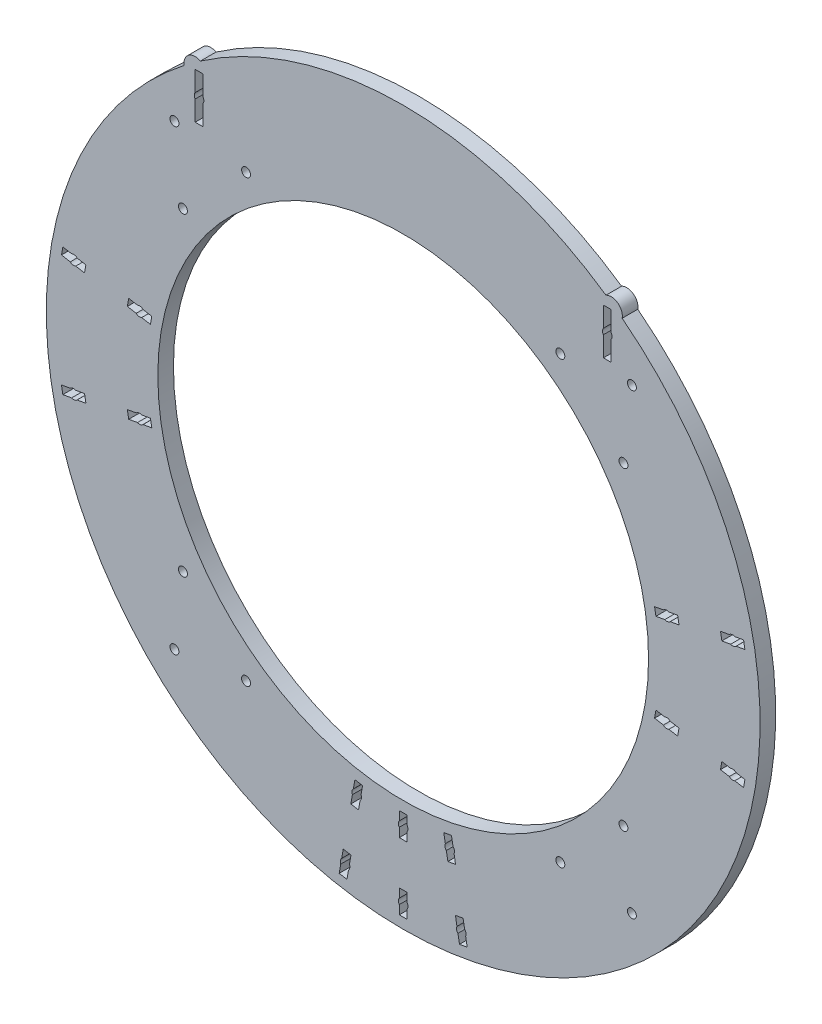
SolidWorks part; units mm, degrees
ref_plane "前视基准面" through (0, 0, 0) normal (0, 0, 1) x (1, 0, 0)
ref_plane "上视基准面" through (0, 0, 0) normal (0, 1, 0) x (1, 0, 0)
ref_plane "右视基准面" through (0, 0, 0) normal (1, 0, 0) x (0, 0, -1)
other "Configuration Table"
sketch "草图1" plane through (0, 0, 0) normal (0, 0, 1) x (1, 0, 0)
  circle A0 centre (0, 0) radius 160
  circle A1 centre (0, 0) radius 110
  dimension "D1" = 320
  dimension "D2" = 220
extrude "凸台-拉伸1" add sketch "草图1" along normal mid plane 7
sketch "草图2" plane through (0, 0, 0) normal (0, 0, 1) x (1, 0, 0)
  line L0 (-1000, 0) -> (49000, 0) construction
  line L1 (0, -1000) -> (0, 49000) construction
  line L2 (-1.75, 148.751) -> (-1.75, 144.75)
  line L3 (-1.75, 155.25) -> (1.75, 155.25)
  line L4 (-1.75, 155.25) -> (-1.75, 151.249)
  line L5 (-1.75, 144.75) -> (1.75, 144.75)
  line L6 (1.75, 155.25) -> (1.75, 151.249)
  line L7 (-1.75, 155.25) -> (1.75, 144.75) construction
  line L8 (-1.75, 144.75) -> (1.75, 155.25) construction
  line L9 (-1.75, 125.25) -> (1.75, 125.25)
  line L10 (-1.75, 125.25) -> (-1.75, 121.249)
  line L11 (-1.75, 114.75) -> (1.75, 114.75)
  line L12 (1.75, 125.25) -> (1.75, 121.249)
  line L13 (-1.75, 125.25) -> (1.75, 114.75) construction
  line L14 (-1.75, 114.75) -> (1.75, 125.25) construction
  line L15 (1.75, 148.751) -> (1.75, 144.75)
  line L16 (-1.75, 118.751) -> (-1.75, 114.75)
  line L17 (1.75, 118.751) -> (1.75, 114.75)
  line L18 (125.25, 1.75) -> (125.25, -1.75)
  line L19 (125.25, -1.75) -> (121.249, -1.75)
  line L20 (118.751, -1.75) -> (114.75, -1.75)
  line L21 (114.75, 1.75) -> (114.75, -1.75)
  line L22 (118.751, 1.75) -> (114.75, 1.75)
  line L23 (125.25, 1.75) -> (121.249, 1.75)
  line L24 (155.25, 1.75) -> (151.249, 1.75)
  line L25 (148.751, 1.75) -> (144.75, 1.75)
  line L26 (144.75, 1.75) -> (144.75, -1.75)
  line L27 (148.751, -1.75) -> (144.75, -1.75)
  line L28 (155.25, -1.75) -> (151.249, -1.75)
  line L29 (155.25, 1.75) -> (155.25, -1.75)
  line L30 (1.75, -125.25) -> (-1.75, -125.25)
  line L31 (-1.75, -125.25) -> (-1.75, -121.249)
  line L32 (-1.75, -118.751) -> (-1.75, -114.75)
  line L33 (1.75, -114.75) -> (-1.75, -114.75)
  line L34 (1.75, -118.751) -> (1.75, -114.75)
  line L35 (1.75, -125.25) -> (1.75, -121.249)
  line L36 (1.75, -155.25) -> (1.75, -151.249)
  line L37 (1.75, -148.751) -> (1.75, -144.75)
  line L38 (1.75, -144.75) -> (-1.75, -144.75)
  line L39 (-1.75, -148.751) -> (-1.75, -144.75)
  line L40 (-1.75, -155.25) -> (-1.75, -151.249)
  line L41 (1.75, -155.25) -> (-1.75, -155.25)
  line L42 (-125.25, -1.75) -> (-125.25, 1.75)
  line L43 (-125.25, 1.75) -> (-121.249, 1.75)
  line L44 (-118.751, 1.75) -> (-114.75, 1.75)
  line L45 (-114.75, -1.75) -> (-114.75, 1.75)
  line L46 (-118.751, -1.75) -> (-114.75, -1.75)
  line L47 (-125.25, -1.75) -> (-121.249, -1.75)
  line L48 (-155.25, -1.75) -> (-151.249, -1.75)
  line L49 (-148.751, -1.75) -> (-144.75, -1.75)
  line L50 (-144.75, -1.75) -> (-144.75, 1.75)
  line L51 (-148.751, 1.75) -> (-144.75, 1.75)
  line L52 (-155.25, 1.75) -> (-151.249, 1.75)
  line L53 (-155.25, -1.75) -> (-155.25, 1.75)
  line L54 (0, 0) -> (1.75, 114.75) construction
  line L55 (25.2355, 153.1953) -> (24.5407, 149.2551)
  line L56 (24.1069, 146.795) -> (23.4122, 142.8548)
  line L57 (23.4122, 142.8548) -> (26.859, 142.247)
  line L58 (27.5538, 146.1873) -> (26.859, 142.247)
  line L59 (28.6823, 152.5875) -> (27.9875, 148.6473)
  line L60 (25.2355, 153.1953) -> (28.6823, 152.5875)
  line L61 (20.026, 123.6511) -> (23.4728, 123.0433)
  line L62 (23.4728, 123.0433) -> (22.7781, 119.1031)
  line L63 (22.3443, 116.643) -> (21.6495, 112.7028)
  line L64 (18.2027, 113.3106) -> (21.6495, 112.7028)
  line L65 (18.8975, 117.2508) -> (18.2027, 113.3106)
  line L66 (20.026, 123.6511) -> (19.3313, 119.7108)
  line L67 (123.6511, -20.026) -> (123.0433, -23.4728)
  line L68 (123.0433, -23.4728) -> (119.1031, -22.7781)
  line L69 (116.643, -22.3443) -> (112.7028, -21.6495)
  line L70 (113.3106, -18.2027) -> (112.7028, -21.6495)
  line L71 (117.2508, -18.8975) -> (113.3106, -18.2027)
  line L72 (123.6511, -20.026) -> (119.7108, -19.3313)
  line L73 (153.1953, -25.2355) -> (149.2551, -24.5407)
  line L74 (146.795, -24.1069) -> (142.8548, -23.4122)
  line L75 (142.8548, -23.4122) -> (142.247, -26.859)
  line L76 (146.1873, -27.5538) -> (142.247, -26.859)
  line L77 (152.5875, -28.6823) -> (148.6473, -27.9875)
  line L78 (153.1953, -25.2355) -> (152.5875, -28.6823)
  line L79 (-25.2355, -153.1953) -> (-24.5407, -149.2551)
  line L80 (-24.1069, -146.795) -> (-23.4122, -142.8548)
  line L81 (-23.4122, -142.8548) -> (-26.859, -142.247)
  line L82 (-27.5538, -146.1873) -> (-26.859, -142.247)
  line L83 (-28.6823, -152.5875) -> (-27.9875, -148.6473)
  line L84 (-25.2355, -153.1953) -> (-28.6823, -152.5875)
  line L85 (-20.026, -123.6511) -> (-23.4728, -123.0433)
  line L86 (-23.4728, -123.0433) -> (-22.7781, -119.1031)
  line L87 (-22.3443, -116.643) -> (-21.6495, -112.7028)
  line L88 (-18.2027, -113.3106) -> (-21.6495, -112.7028)
  line L89 (-18.8975, -117.2508) -> (-18.2027, -113.3106)
  line L90 (-20.026, -123.6511) -> (-19.3313, -119.7108)
  line L91 (-123.6511, 20.026) -> (-123.0433, 23.4728)
  line L92 (-123.0433, 23.4728) -> (-119.1031, 22.7781)
  line L93 (-116.643, 22.3443) -> (-112.7028, 21.6495)
  line L94 (-113.3106, 18.2027) -> (-112.7028, 21.6495)
  line L95 (-117.2508, 18.8975) -> (-113.3106, 18.2027)
  line L96 (-123.6511, 20.026) -> (-119.7108, 19.3313)
  line L97 (-153.1953, 25.2355) -> (-149.2551, 24.5407)
  line L98 (-146.795, 24.1069) -> (-142.8548, 23.4122)
  line L99 (-142.8548, 23.4122) -> (-142.247, 26.859)
  line L100 (-146.1873, 27.5538) -> (-142.247, 26.859)
  line L101 (-152.5875, 28.6823) -> (-148.6473, 27.9875)
  line L102 (-153.1953, 25.2355) -> (-152.5875, 28.6823)
  line L103 (20.026, -123.6511) -> (19.3313, -119.7108)
  line L104 (18.8975, -117.2508) -> (18.2027, -113.3106)
  line L105 (18.2027, -113.3106) -> (21.6495, -112.7028)
  line L106 (22.3443, -116.643) -> (21.6495, -112.7028)
  line L107 (23.4728, -123.0433) -> (22.7781, -119.1031)
  line L108 (20.026, -123.6511) -> (23.4728, -123.0433)
  line L109 (25.2355, -153.1953) -> (28.6823, -152.5875)
  line L110 (28.6823, -152.5875) -> (27.9875, -148.6473)
  line L111 (27.5538, -146.1873) -> (26.859, -142.247)
  line L112 (23.4122, -142.8548) -> (26.859, -142.247)
  line L113 (24.1069, -146.795) -> (23.4122, -142.8548)
  line L114 (25.2355, -153.1953) -> (24.5407, -149.2551)
  line L115 (153.1953, 25.2355) -> (152.5875, 28.6823)
  line L116 (152.5875, 28.6823) -> (148.6473, 27.9875)
  line L117 (146.1873, 27.5538) -> (142.247, 26.859)
  line L118 (142.8548, 23.4122) -> (142.247, 26.859)
  line L119 (146.795, 24.1069) -> (142.8548, 23.4122)
  line L120 (153.1953, 25.2355) -> (149.2551, 24.5407)
  line L121 (123.6511, 20.026) -> (119.7108, 19.3313)
  line L122 (117.2508, 18.8975) -> (113.3106, 18.2027)
  line L123 (113.3106, 18.2027) -> (112.7028, 21.6495)
  line L124 (116.643, 22.3443) -> (112.7028, 21.6495)
  line L125 (123.0433, 23.4728) -> (119.1031, 22.7781)
  line L126 (123.6511, 20.026) -> (123.0433, 23.4728)
  line L127 (-153.1953, -25.2355) -> (-152.5875, -28.6823)
  line L128 (-152.5875, -28.6823) -> (-148.6473, -27.9875)
  line L129 (-146.1873, -27.5538) -> (-142.247, -26.859)
  line L130 (-142.8548, -23.4122) -> (-142.247, -26.859)
  line L131 (-146.795, -24.1069) -> (-142.8548, -23.4122)
  line L132 (-153.1953, -25.2355) -> (-149.2551, -24.5407)
  line L133 (-123.6511, -20.026) -> (-119.7108, -19.3313)
  line L134 (-117.2508, -18.8975) -> (-113.3106, -18.2027)
  line L135 (-113.3106, -18.2027) -> (-112.7028, -21.6495)
  line L136 (-116.643, -22.3443) -> (-112.7028, -21.6495)
  line L137 (-123.0433, -23.4728) -> (-119.1031, -22.7781)
  line L138 (-123.6511, -20.026) -> (-123.0433, -23.4728)
  line L139 (-20.026, 123.6511) -> (-19.3313, 119.7108)
  line L140 (-18.8975, 117.2508) -> (-18.2027, 113.3106)
  line L141 (-18.2027, 113.3106) -> (-21.6495, 112.7028)
  line L142 (-22.3443, 116.643) -> (-21.6495, 112.7028)
  line L143 (-23.4728, 123.0433) -> (-22.7781, 119.1031)
  line L144 (-20.026, 123.6511) -> (-23.4728, 123.0433)
  line L145 (-25.2355, 153.1953) -> (-28.6823, 152.5875)
  line L146 (-28.6823, 152.5875) -> (-27.9875, 148.6473)
  line L147 (-27.5538, 146.1873) -> (-26.859, 142.247)
  line L148 (-23.4122, 142.8548) -> (-26.859, 142.247)
  line L149 (-24.1069, 146.795) -> (-23.4122, 142.8548)
  line L150 (-25.2355, 153.1953) -> (-24.5407, 149.2551)
  circle A0 centre (0, 0) radius 160 construction
  arc A1 (-1.75, 121.249) -> (-1.75, 118.751) centre (0, 120) ccw
  arc A2 (-1.75, 151.249) -> (-1.75, 148.751) centre (0, 150) ccw
  arc A3 (1.75, 148.751) -> (1.75, 151.249) centre (0, 150) ccw
  arc A4 (1.75, 118.751) -> (1.75, 121.249) centre (0, 120) ccw
  arc A5 (118.751, -1.75) -> (121.249, -1.75) centre (120, 0) ccw
  arc A6 (121.249, 1.75) -> (118.751, 1.75) centre (120, 0) ccw
  arc A7 (151.249, 1.75) -> (148.751, 1.75) centre (150, 0) ccw
  arc A8 (148.751, -1.75) -> (151.249, -1.75) centre (150, 0) ccw
  arc A9 (-1.75, -118.751) -> (-1.75, -121.249) centre (0, -120) ccw
  arc A10 (1.75, -121.249) -> (1.75, -118.751) centre (0, -120) ccw
  arc A11 (1.75, -151.249) -> (1.75, -148.751) centre (0, -150) ccw
  arc A12 (-1.75, -148.751) -> (-1.75, -151.249) centre (0, -150) ccw
  arc A13 (-118.751, 1.75) -> (-121.249, 1.75) centre (-120, 0) ccw
  arc A14 (-121.249, -1.75) -> (-118.751, -1.75) centre (-120, 0) ccw
  arc A15 (-151.249, -1.75) -> (-148.751, -1.75) centre (-150, 0) ccw
  arc A16 (-148.751, 1.75) -> (-151.249, 1.75) centre (-150, 0) ccw
  arc A17 (24.5407, 149.2551) -> (24.1069, 146.795) centre (26.0472, 147.7212) ccw
  arc A18 (27.5538, 146.1873) -> (27.9875, 148.6473) centre (26.0472, 147.7212) ccw
  arc A19 (22.3443, 116.643) -> (22.7781, 119.1031) centre (20.8378, 118.1769) ccw
  arc A20 (19.3313, 119.7108) -> (18.8975, 117.2508) centre (20.8378, 118.1769) ccw
  arc A21 (116.643, -22.3443) -> (119.1031, -22.7781) centre (118.1769, -20.8378) ccw
  arc A22 (119.7108, -19.3313) -> (117.2508, -18.8975) centre (118.1769, -20.8378) ccw
  arc A23 (149.2551, -24.5407) -> (146.795, -24.1069) centre (147.7212, -26.0472) ccw
  arc A24 (146.1873, -27.5538) -> (148.6473, -27.9875) centre (147.7212, -26.0472) ccw
  arc A25 (-24.5407, -149.2551) -> (-24.1069, -146.795) centre (-26.0472, -147.7212) ccw
  arc A26 (-27.5538, -146.1873) -> (-27.9875, -148.6473) centre (-26.0472, -147.7212) ccw
  arc A27 (-22.3443, -116.643) -> (-22.7781, -119.1031) centre (-20.8378, -118.1769) ccw
  arc A28 (-19.3313, -119.7108) -> (-18.8975, -117.2508) centre (-20.8378, -118.1769) ccw
  arc A29 (-116.643, 22.3443) -> (-119.1031, 22.7781) centre (-118.1769, 20.8378) ccw
  arc A30 (-119.7108, 19.3313) -> (-117.2508, 18.8975) centre (-118.1769, 20.8378) ccw
  arc A31 (-149.2551, 24.5407) -> (-146.795, 24.1069) centre (-147.7212, 26.0472) ccw
  arc A32 (-146.1873, 27.5538) -> (-148.6473, 27.9875) centre (-147.7212, 26.0472) ccw
  arc A33 (19.3313, -119.7108) -> (18.8975, -117.2508) centre (20.8378, -118.1769) cw
  arc A34 (22.3443, -116.643) -> (22.7781, -119.1031) centre (20.8378, -118.1769) cw
  arc A35 (27.5538, -146.1873) -> (27.9875, -148.6473) centre (26.0472, -147.7212) cw
  arc A36 (24.5407, -149.2551) -> (24.1069, -146.795) centre (26.0472, -147.7212) cw
  arc A37 (146.1873, 27.5538) -> (148.6473, 27.9875) centre (147.7212, 26.0472) cw
  arc A38 (149.2551, 24.5407) -> (146.795, 24.1069) centre (147.7212, 26.0472) cw
  arc A39 (119.7108, 19.3313) -> (117.2508, 18.8975) centre (118.1769, 20.8378) cw
  arc A40 (116.643, 22.3443) -> (119.1031, 22.7781) centre (118.1769, 20.8378) cw
  arc A41 (-146.1873, -27.5538) -> (-148.6473, -27.9875) centre (-147.7212, -26.0472) cw
  arc A42 (-149.2551, -24.5407) -> (-146.795, -24.1069) centre (-147.7212, -26.0472) cw
  arc A43 (-119.7108, -19.3313) -> (-117.2508, -18.8975) centre (-118.1769, -20.8378) cw
  arc A44 (-116.643, -22.3443) -> (-119.1031, -22.7781) centre (-118.1769, -20.8378) cw
  arc A45 (-19.3313, 119.7108) -> (-18.8975, 117.2508) centre (-20.8378, 118.1769) cw
  arc A46 (-22.3443, 116.643) -> (-22.7781, 119.1031) centre (-20.8378, 118.1769) cw
  arc A47 (-27.5538, 146.1873) -> (-27.9875, 148.6473) centre (-26.0472, 147.7212) cw
  arc A48 (-24.5407, 149.2551) -> (-24.1069, 146.795) centre (-26.0472, 147.7212) cw
  point P4 (0, 150)
  point P12 (0, 160)
  point P14 (0, 120)
  point P159 (0, 0)
  dimension "D7" = 4.3
  dimension "D8" = 4.3
  dimension "D1" = 10.5
  dimension "D2" = 3.5
  dimension "D3" = 10
  dimension "D4" = 10.5
  dimension "D5" = 3.5
  dimension "D6" = 19.5
  dimension "D10" = 2
  dimension "D11" = 10
  dimension "D9" = 4
extrude "切除-拉伸1" cut sketch "草图2" against normal through all both and the other way through all contours L82 A26 L83 L84 L79 A25 L80 L81 | L35 A10 L34 L33 L32 A9 L31 L30 | L39 A12 L40 L41 L36 A11 L37 L38 | A36 L114 L109 L110 A35 L111 L112 L113 | L76 A24 L77 L78 L73 A23 L74 L75 | L72 A22 L71 L70 L69 A21 L68 L67 | A38 L120 L115 L116 A37 L117 L118 L119 | A40 L124 L123 L122 A39 L121 L126 L125 | A42 L132 L127 L128 A41 L129 L130 L131 | A44 L136 L135 L134 A43 L133 L138 L137 | L96 A30 L95 L94 L93 A29 L92 L91 | L86 A27 L87 L88 L89 A28 L90 L85 | L107 A34 L106 L105 L104 A33 L103 L108 | L100 L99 L98 A31 L97 L102 L101 A32
sketch "草图3" plane through (0, 0, 3.5) normal (0, 0, 1) x (1, 0, 0)
  circle A1 centre (-102.5305, 102.5305) radius 2
  circle A4 centre (-70.4539, 98.7382) radius 2
  circle A5 centre (-98.7382, 70.4539) radius 2
  circle A6 centre (102.5305, 102.5305) radius 2
  circle A7 centre (98.7382, 70.4539) radius 2
  circle A8 centre (70.4539, 98.7382) radius 2
  circle A9 centre (102.5305, -102.5305) radius 2
  circle A10 centre (70.4539, -98.7382) radius 2
  circle A11 centre (98.7382, -70.4539) radius 2
  circle A12 centre (-102.5305, -102.5305) radius 2
  circle A13 centre (-98.7382, -70.4539) radius 2
  circle A14 centre (-70.4539, -98.7382) radius 2
  point P27 (0, 0)
  dimension "D1" = 4
extrude "切除-拉伸2" cut sketch "草图3" against normal through all both and the other way through all
sketch "草图4" plane through (0, 0, -3.5) normal (0, 0, -1) x (-1, 0, 0)
  line L0 (-93, 127) -> (-90, 107) construction
  line L3 (0, 3.85) -> (0, -3.85) construction
  line L4 (93.25, 106.75) -> (89.75, 106.75)
  line L5 (-93.25, 127.25) -> (-89.75, 127.25)
  line L6 (-93.25, 127.25) -> (-93.25, 106.75)
  line L7 (-93.25, 106.75) -> (-89.75, 106.75)
  line L12 (-89.75, 127.25) -> (-89.75, 106.75)
  line L13 (-93.25, 127.25) -> (-89.75, 106.75) construction
  line L14 (-93.25, 106.75) -> (-89.75, 127.25) construction
  line L15 (89.75, 127.25) -> (89.75, 106.75)
  line L22 (93.25, 127.25) -> (89.75, 127.25)
  line L23 (93.25, 127.25) -> (93.25, 106.75)
  circle A4 centre (-91.5, 117) radius 2.15
  circle A5 centre (91.5, 117) radius 2.15
  point P4 (-91.5, 117)
  dimension "D3" = 4.3
  dimension "D1" = 20.5
  dimension "D2" = 3.5
extrude "切除-拉伸3" cut sketch "草图4" against normal through all both and the other way through all contours A4 L6 L7 L12 | L12 A4 L6 | L6 A4 | A4 L12 L5 L6 | L12 A4 | L23 A5 L15 L4 | L15 A5 L23 L22
sketch "草图5" plane through (0, 0, 3.5) normal (0, 0, 1) x (1, 0, 0)
  line L0 (93.25, 127.25) -> (93.25, 118.249) construction
  line L1 (93.25, 127.25) -> (89.75, 127.25) construction
  arc A0 (-90.9061, 131.6666) -> (-98.1675, 126.3453) centre (-93.25, 127.25) ccw
  arc A1 (98.1675, 126.3453) -> (90.9061, 131.6666) centre (93.25, 127.25) ccw
  circle A2 centre (0, 0) radius 160 construction
  arc A3 (-90.9061, 131.6666) -> (-98.1675, 126.3453) centre (0, 0) ccw
  arc A4 (98.1675, 126.3453) -> (90.9061, 131.6666) centre (0, 0) ccw
  dimension "D1" = 10
  dimension "D2" = 10
extrude "凸台-拉伸2" add sketch "草图5" against normal blind 7
